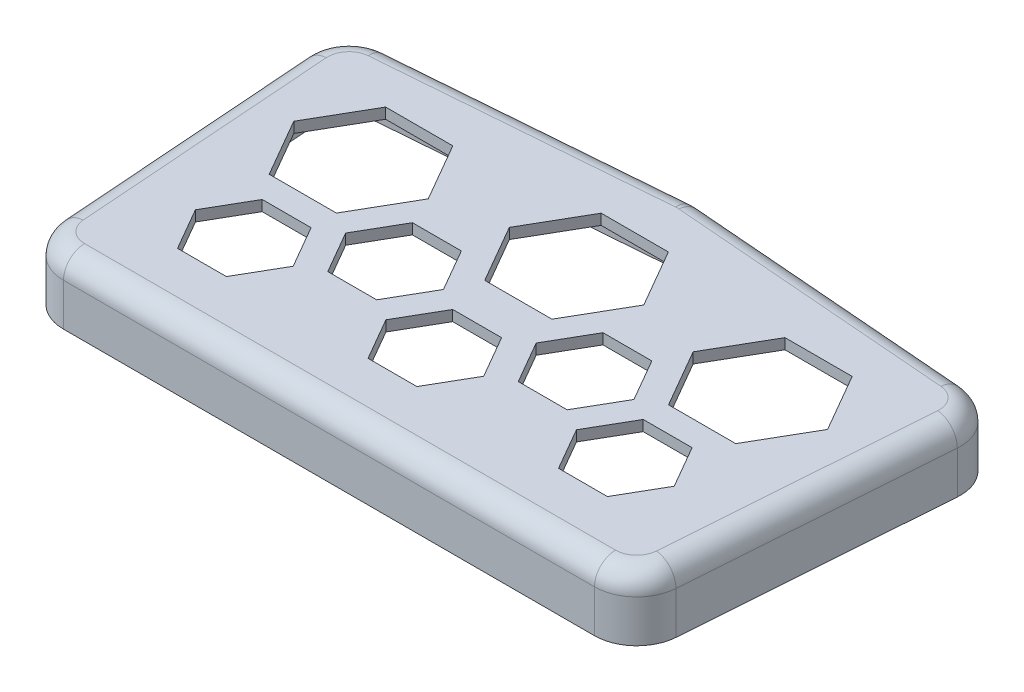
SolidWorks part; units mm, degrees
material "ABS"
ref_plane "Front Plane" through (0, 0, 0) normal (0, 0, 1) x (1, 0, 0)
ref_plane "Top Plane" through (0, 0, 0) normal (0, 1, 0) x (1, 0, 0)
ref_plane "Right Plane" through (0, 0, 0) normal (1, 0, 0) x (0, 0, -1)
sketch "Sketch1" plane through (0, 0, 0) normal (0, 1, 0) x (1, 0, 0)
  line L0 (-119.7993, 75.5161) -> (0, 85.0411) construction
  line L5 (114.3, -63.5) -> (-114.3, -63.5)
  line L6 (-187.1321, -5.3038) -> (-197.9001, 142.5619)
  line L15 (-197.9001, 142.5619) -> (0, 158.2966)
  line L16 (0, 158.2966) -> (197.9001, 142.5619)
  line L17 (-114.3, 0) -> (-119.7993, 75.5161) construction
  line L18 (0, 85.0411) -> (119.7993, 75.5161) construction
  line L19 (119.7993, 75.5161) -> (114.3, 0) construction
  line L20 (114.3, 0) -> (-114.3, 0) construction
  line L21 (197.9001, 142.5619) -> (187.1321, -5.3038)
  line L22 (-187.1321, -5.3038) -> (-182.8942, -63.5)
  line L23 (-182.8942, -63.5) -> (-114.3, -63.5)
  line L24 (114.3, -63.5) -> (182.8942, -63.5)
  line L25 (182.8942, -63.5) -> (187.1321, -5.3038)
  point P0 (0, 0)
  dimension "D1" = 63.5
  dimension "D2" = 73.025
extrude "Boss-Extrude1" add sketch "Sketch1" along normal blind 38.1
fillet "Fillet1" radius 25.4 5 edges at (182.8942, 19.05, 63.5) (197.9001, 19.05, -142.5619) (-182.8942, 19.05, 63.5) (0, 19.05, -158.2966) (-197.9001, 19.05, -142.5619)
fillet "Fillet2" radius 12.7 10 edges at (190.3385, 38.1, -38.726) (-190.3385, 38.1, -38.726) (-87.3804, 38.1, -151.3491) (87.3804, 38.1, -151.3491) (0, 38.1, 63.5) (-176.5726, 38.1, 56.7013) (-190.0072, 38.1, -135.7863) (0, 38.1, -158.2164) (190.0072, 38.1, -135.7863) (176.5726, 38.1, 56.7013)
shell "Shell1" thickness 6.35
sketch "Sketch3" plane through (0, 38.1, 0) normal (0, 1, 0) x (1, 0, 0)
  line L0 (-96.3031, 10.3905) -> (-79.0335, 20.3611) construction
  line L1 (-128.9647, 25.4) -> (-143.6294, 0)
  line L2 (-119.7993, 75.5161) -> (0, 85.0411) construction
  line L3 (-27.8206, 32.9956) -> (-42.4853, 58.3956)
  line L4 (-42.4853, 58.3956) -> (-71.8147, 58.3956)
  line L5 (-71.8147, 58.3956) -> (-86.4794, 32.9956)
  line L6 (-86.4794, 32.9956) -> (-71.8147, 7.5956)
  line L7 (-71.8147, 7.5956) -> (-42.4853, 7.5956)
  line L8 (-42.4853, 7.5956) -> (-27.8206, 32.9956)
  line L9 (40.3279, 85.0411) -> (20.164, 119.9661)
  line L10 (-99.6353, -25.4) -> (-84.9706, 0)
  line L11 (-84.9706, 0) -> (-99.6353, 25.4)
  line L12 (-99.6353, 25.4) -> (-128.9647, 25.4)
  line L13 (-143.6294, 0) -> (-128.9647, -25.4)
  line L14 (-128.9647, -25.4) -> (-99.6353, -25.4)
  line L15 (20.164, 119.9661) -> (-20.164, 119.9661)
  line L16 (-20.164, 119.9661) -> (-40.3279, 85.0411)
  line L17 (-40.3279, 85.0411) -> (-20.164, 50.1161)
  line L18 (-20.164, 50.1161) -> (20.164, 50.1161)
  line L19 (20.164, 50.1161) -> (40.3279, 85.0411)
  line L22 (29.3294, 0) -> (14.6647, 25.4)
  line L23 (14.6647, 25.4) -> (-14.6647, 25.4)
  line L24 (-14.6647, 25.4) -> (-29.3294, 0)
  line L25 (-29.3294, 0) -> (-14.6647, -25.4)
  line L26 (-14.6647, -25.4) -> (14.6647, -25.4)
  line L27 (14.6647, -25.4) -> (29.3294, 0)
  line L29 (143.6294, 0) -> (128.9647, 25.4)
  line L30 (128.9647, 25.4) -> (99.6353, 25.4)
  line L31 (99.6353, 25.4) -> (84.9706, 0)
  line L32 (84.9706, 0) -> (99.6353, -25.4)
  line L33 (99.6353, -25.4) -> (128.9647, -25.4)
  line L34 (128.9647, -25.4) -> (143.6294, 0)
  line L35 (12.0635, 6.9649) -> (33.9613, 19.6075) construction
  line L38 (71.8147, 7.5956) -> (86.4794, 32.9956)
  line L39 (86.4794, 32.9956) -> (71.8147, 58.3956)
  line L40 (71.8147, 58.3956) -> (42.4853, 58.3956)
  line L41 (42.4853, 58.3956) -> (27.8206, 32.9956)
  line L42 (27.8206, 32.9956) -> (42.4853, 7.5956)
  line L43 (42.4853, 7.5956) -> (71.8147, 7.5956)
  line L44 (-114.3, 0) -> (-119.7993, 75.5161) construction
  line L45 (-99.6353, 40.5911) -> (-79.4713, 75.5161)
  line L46 (-79.4713, 75.5161) -> (-99.6353, 110.4411)
  line L47 (-99.6353, 110.4411) -> (-139.9632, 110.4411)
  line L48 (-139.9632, 110.4411) -> (-160.1272, 75.5161)
  line L49 (-160.1272, 75.5161) -> (-139.9632, 40.5911)
  line L50 (-139.9632, 40.5911) -> (-99.6353, 40.5911)
  line L51 (160.1272, 75.5161) -> (139.9632, 110.4411)
  line L52 (139.9632, 110.4411) -> (99.6353, 110.4411)
  line L53 (99.6353, 110.4411) -> (79.4713, 75.5161)
  line L54 (79.4713, 75.5161) -> (99.6353, 40.5911)
  line L55 (99.6353, 40.5911) -> (139.9632, 40.5911)
  line L56 (139.9632, 40.5911) -> (160.1272, 75.5161)
  line L57 (0, 85.0411) -> (119.7993, 75.5161) construction
  line L58 (119.7993, 75.5161) -> (114.3, 0) construction
  line L59 (114.3, 0) -> (-114.3, 0) construction
  circle A16 centre (-114.3, 0) radius 25.4 construction
  circle A17 centre (-57.15, 32.9956) radius 25.4 construction
  circle A18 centre (0, 85.0411) radius 34.925 construction
  circle A19 centre (0, 0) radius 25.4 construction
  circle A20 centre (114.3, 0) radius 25.4 construction
  circle A21 centre (57.15, 32.9956) radius 25.4 construction
  circle A22 centre (-119.7993, 75.5161) radius 34.925 construction
  circle A23 centre (119.7993, 75.5161) radius 34.925 construction
  dimension "2.5" = 69.85
  dimension "D1" = 114.3
  dimension "D2" = 50.8
  dimension "D3" = 114.3
  dimension "D4" = 57.15
  dimension "D5" = 15.1911
  dimension "D6" = 15.1911
  dimension "D7" = 15.1911
  dimension "D8" = 15.1911
  dimension "D9" = 15.1911
  dimension "D10" = 15.1911
extrude "Cut-Extrude1" cut sketch "Sketch3" against normal through all both and the other way through all
equation "\"D4@Sketch3\"=\"D1@Sketch3\"/2"
equation "\"D3@Sketch3\"=\"D1@Sketch3\""
equation "\"D6@Sketch3\"=\"D5@Sketch3\""
equation "\"D7@Sketch3\"=\"D6@Sketch3\""
equation "\"D8@Sketch3\"=\"D6@Sketch3\""
equation "\"D9@Sketch3\"=\"D6@Sketch3\""
equation "\"D10@Sketch3\"=\"D9@Sketch3\""
